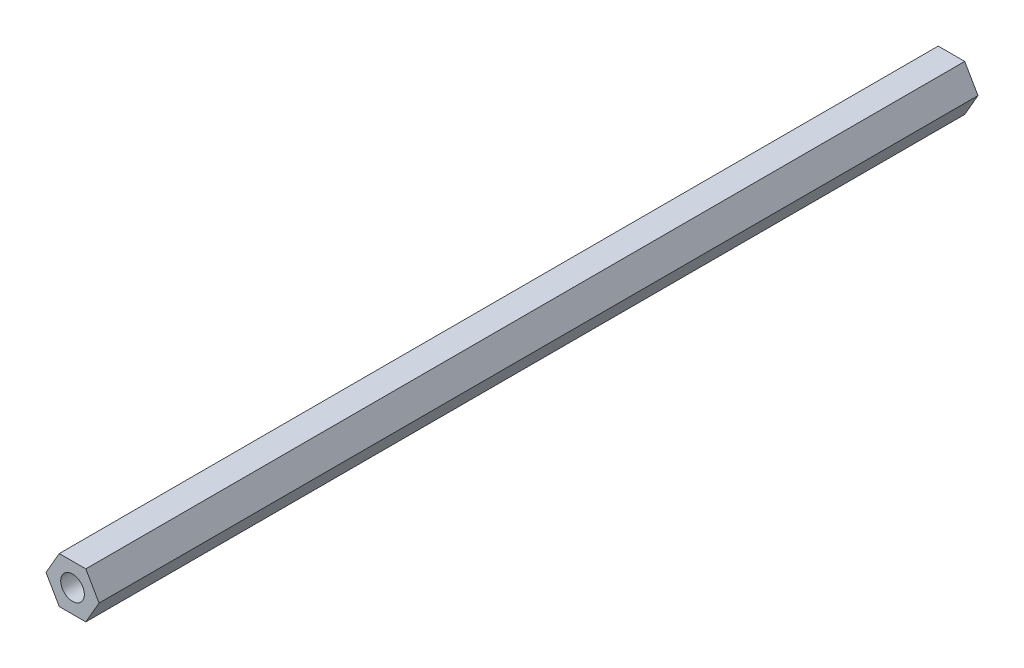
SolidWorks part; units mm, degrees
material "6061 Alloy"
ref_plane "Front Plane" through (0, 0, 0) normal (0, 0, 1) x (1, 0, 0)
ref_plane "Top Plane" through (0, 0, 0) normal (0, 1, 0) x (1, 0, 0)
ref_plane "Right Plane" through (0, 0, 0) normal (1, 0, 0) x (0, 0, -1)
sketch "Sketch1" plane through (0, 0, 0) normal (0, 0, 1) x (1, 0, 0)
  line L1 (-3.6662, 6.35) -> (-7.3323, 0)
  line L2 (-7.3323, 0) -> (-3.6662, -6.35)
  line L3 (-3.6662, -6.35) -> (3.6662, -6.35)
  line L4 (3.6662, -6.35) -> (7.3323, 0)
  line L5 (7.3323, 0) -> (3.6662, 6.35)
  line L6 (3.6662, 6.35) -> (-3.6662, 6.35)
  circle A0 centre (0, 0) radius 6.35 construction
  circle A1 centre (0, 0) radius 3.2639
  dimension "D1" = 12.7
  dimension "D2" = 6.5278
extrude "Boss-Extrude1" add sketch "Sketch1" along normal blind 242.8875
